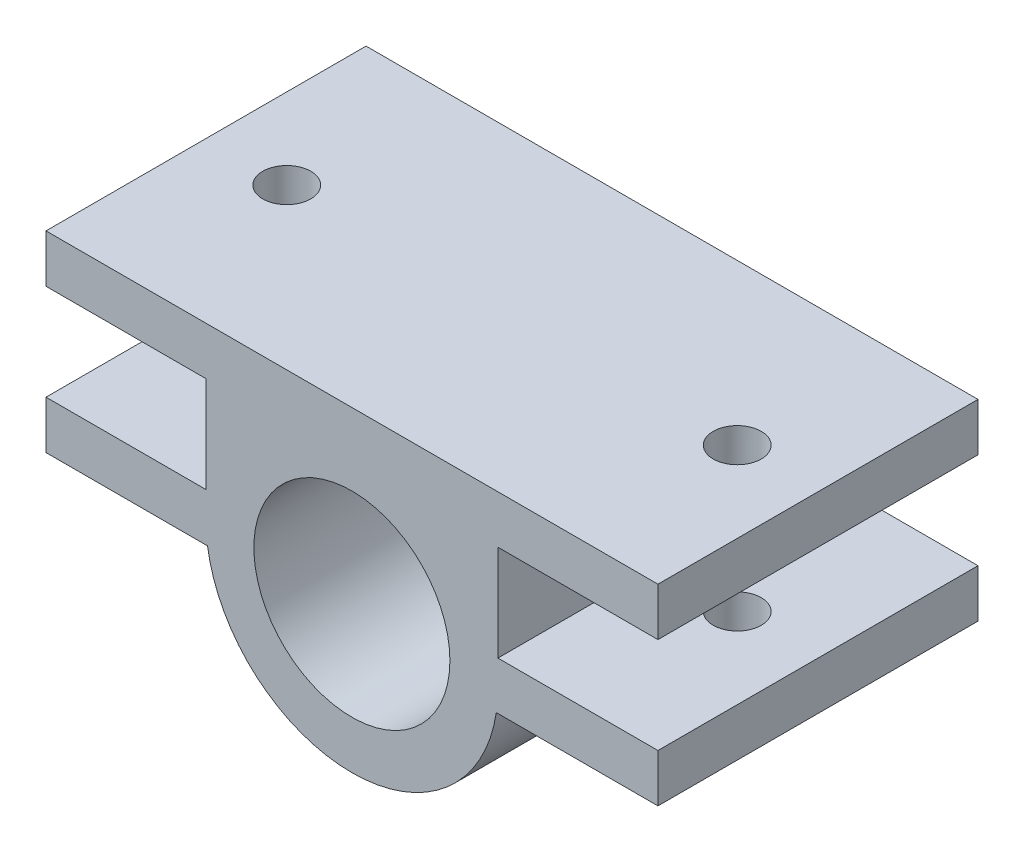
SolidWorks part; units mm, degrees
ref_plane "Plan de face" through (0, 0, 0) normal (0, 0, 1) x (1, 0, 0)
ref_plane "Plan de dessus" through (0, 0, 0) normal (0, 1, 0) x (1, 0, 0)
ref_plane "Plan de droite" through (0, 0, 0) normal (1, 0, 0) x (0, 0, -1)
sketch "Esquisse1" plane through (0, 0, 0) normal (0, 0, 1) x (1, 0, 0)
  line L0 (-19.1151, -1.36) -> (0.0099, -1.36)
  line L1 (-19.1151, 1.64) -> (-19.1151, -1.36)
  line L2 (0.0049, 10.64) -> (0.0049, -2.9492) construction
  line L3 (-19.1151, 1.64) -> (-9.1151, 1.64)
  line L4 (-9.1151, 7.64) -> (-9.1151, 1.64)
  line L5 (-9.1151, 7.64) -> (-19.1151, 7.64)
  line L6 (-19.1151, 7.64) -> (-19.1151, 10.64)
  line L8 (-9.125, 0.3) -> (-9.1201, 0.3) construction
  line L23 (9.125, 0.3) -> (9.125, 0)
  line L24 (19.125, 1.64) -> (19.125, -1.36)
  line L25 (19.125, -1.36) -> (0, -1.36)
  line L27 (19.125, 1.64) -> (9.125, 1.64)
  line L28 (9.125, 7.64) -> (19.125, 7.64)
  line L29 (9.125, 7.64) -> (9.125, 1.64)
  line L30 (19.125, 7.64) -> (19.125, 10.64)
  line L31 (19.125, 10.64) -> (-19.1151, 10.64)
  circle A0 centre (0, 0) radius 6.125
  circle A1 centre (0, 0) radius 9.125
  point P14 (0.0049, 10.64)
  dimension "D1" = 12.25
  dimension "D2" = 3
  dimension "D5" = 10
  dimension "D6" = 6
  dimension "D8" = 3
  dimension "D10" = 3
extrude "Boss.-Extru.1" add sketch "Esquisse1" along normal blind 20
sketch "Esquisse2" plane through (0, -1.36, 0) normal (0, -1, 0) x (1, 0, 0)
  line L0 (-19.1151, 20) -> (-9.0231, 20) construction
  line L3 (19.125, 20) -> (19.125, 0) construction
  line L13 (-19.1151, 20) -> (-19.1151, 0) construction
  line L14 (19.125, 20) -> (9.0231, 20) construction
  circle A6 centre (-14.0701, 10) radius 1.5
  circle A7 centre (14.08, 10) radius 1.5
  point P4 (14.824, 9.613)
  point P8 (0, 0)
  point P12 (18.4443, 9.2369)
  dimension "D1" = 5.045
  dimension "D2" = 10
  dimension "D7" = 3
  dimension "D3" = 10
  dimension "D4" = 5.045
extrude "Enlèv. mat.-Extru.1" cut sketch "Esquisse2" against normal through all both and the other way through all
